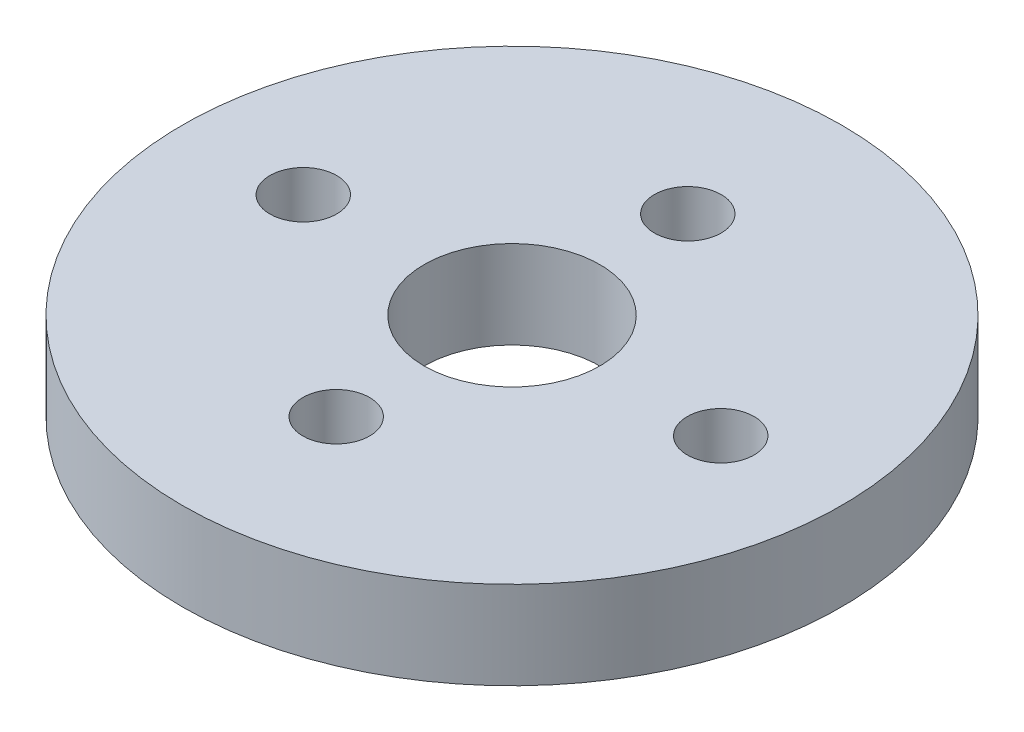
SolidWorks part; units mm, degrees
ref_plane "Front" through (0, 0, 0) normal (0, 0, 1) x (1, 0, 0)
ref_plane "Top" through (0, 0, 0) normal (0, 1, 0) x (1, 0, 0)
ref_plane "Right" through (0, 0, 0) normal (1, 0, 0) x (0, 0, -1)
sketch "草图1" plane through (0, 0, 0) normal (0, 1, 0) x (1, 0, 0)
  circle A0 centre (0, 0) radius 15
extrude "凸台-拉伸1" add sketch "草图1" along normal blind 4
sketch "草图2" plane through (0, 4, 0) normal (0, 1, 0) x (1, 0, 0)
  line L0 (0, 8) -> (0, -8) construction
  line L1 (-9.5, 0) -> (9.5, 0) construction
  circle A0 centre (-9.5, 0) radius 1.52
  circle A1 centre (0, -8) radius 1.52
  circle A2 centre (9.5, 0) radius 1.52
  circle A3 centre (0, 8) radius 1.52
  circle A4 centre (0, 0) radius 4
extrude "切除-拉伸1" cut sketch "草图2" against normal blind 4
ref_plane "基准面1" through (0, 0, -15) normal (0, 0, -1) x (-1, 0, 0)
